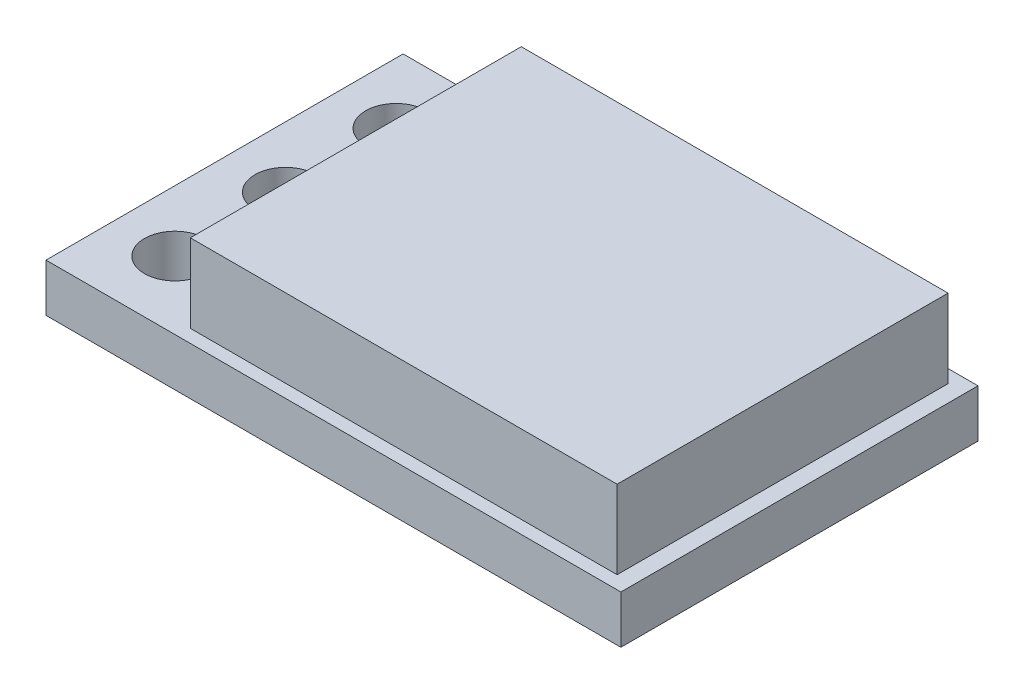
SolidWorks part; units mm, degrees
ref_plane "Спереди" through (0, 0, 0) normal (0, 0, 1) x (1, 0, 0)
ref_plane "Сверху" through (0, 0, 0) normal (0, 1, 0) x (1, 0, 0)
ref_plane "Справа" through (0, 0, 0) normal (1, 0, 0) x (0, 0, -1)
sketch "Эскиз1" plane through (0, 0, 0) normal (0, 1, 0) x (1, 0, 0)
  line L1 (-6.6, 4.1) -> (6.6, 4.1)
  line L2 (-6.6, 4.1) -> (-6.6, -4.1)
  line L3 (-6.6, -4.1) -> (6.6, -4.1)
  line L4 (6.6, 4.1) -> (6.6, -4.1)
  line L5 (-6.6, 4.1) -> (6.6, -4.1) construction
  line L6 (-6.6, -4.1) -> (6.6, 4.1) construction
  point P0 (0, 0)
  dimension "D1" = 13.2
  dimension "D2" = 8.2
extrude "Бобышка-Вытянуть1" add sketch "Эскиз1" along normal blind 1.1
sketch "Эскиз3" plane through (0, 1.1, 0) normal (0, 1, 0) x (1, 0, 0)
  line L1 (-3.5868, 3.8) -> (6.2132, 3.8)
  line L2 (-3.5868, 3.8) -> (-3.5868, -3.8)
  line L3 (-3.5868, -3.8) -> (6.2132, -3.8)
  line L4 (6.2132, 3.8) -> (6.2132, -3.8)
  line L5 (-3.5868, 3.8) -> (6.2132, -3.8) construction
  line L6 (-3.5868, -3.8) -> (6.2132, 3.8) construction
  point P0 (1.3132, 0)
  dimension "D1" = 9.8
  dimension "D2" = 7.6
extrude "Бобышка-Вытянуть2" add sketch "Эскиз3" along normal blind 1.8
sketch "Эскиз2" plane through (0, 1.1, 0) normal (0, 1, 0) x (1, 0, 0)
  line L0 (-6.6, 4.1) -> (-6.6, -4.1) construction
  circle A0 centre (-5.2, -2.54) radius 0.7
  circle A1 centre (-5.2, 0) radius 0.7
  circle A2 centre (-5.2, 2.54) radius 0.7
  dimension "D3" = 1.4
  dimension "D2" = 2.54
  dimension "D4" = 1.4
  dimension "D1" = 3
extrude "Вырез-Вытянуть1" cut sketch "Эскиз2" against normal through all
